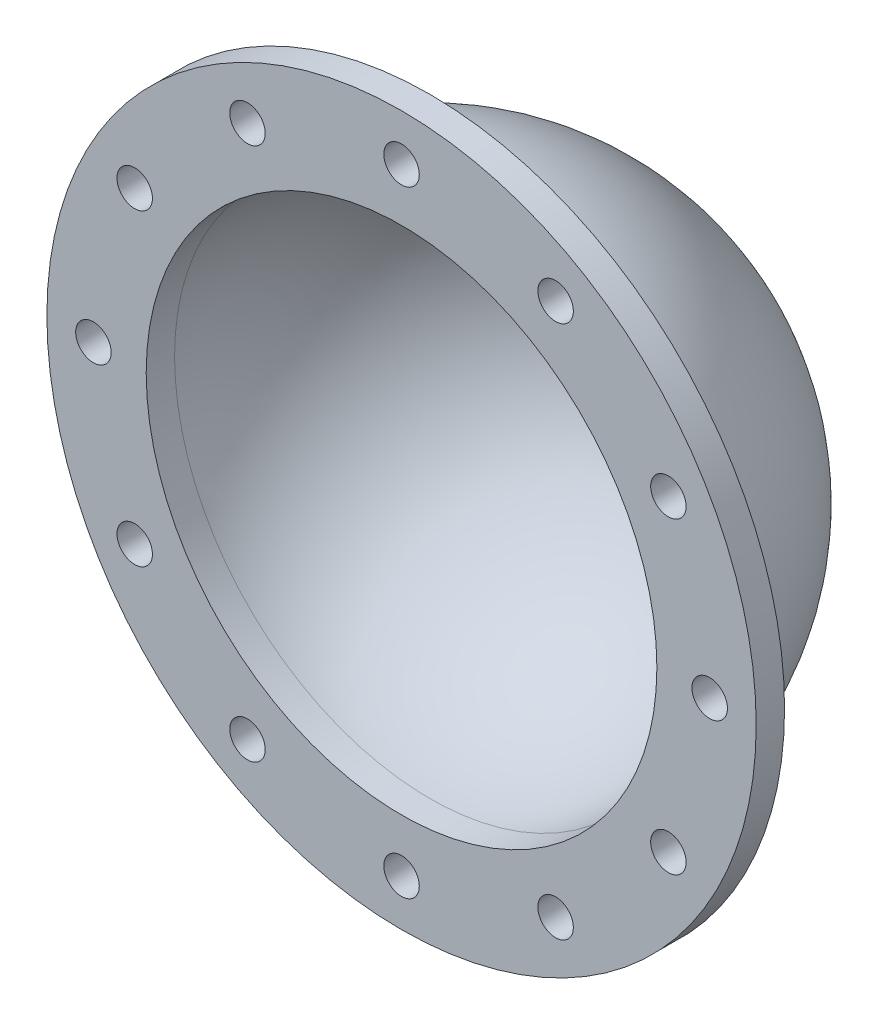
SolidWorks part; units mm, degrees
ref_plane "Front Plane" through (0, 0, 0) normal (0, 0, 1) x (1, 0, 0)
ref_plane "Top Plane" through (0, 0, 0) normal (0, 1, 0) x (1, 0, 0)
ref_plane "Right Plane" through (0, 0, 0) normal (1, 0, 0) x (0, 0, -1)
sketch "Sketch1" plane through (0, 0, 0) normal (0, 0, 1) x (1, 0, 0)
  line L0 (0, 250) -> (0, 229.7001) construction
  line L1 (0, 229.7001) -> (0, 204.7001) construction
  circle A0 centre (0, 0) radius 250
  circle A1 centre (0, 0) radius 180
  circle A2 centre (0, 217.2001) radius 12.5
  circle A3 centre (108.6, 188.1008) radius 12.5
  circle A4 centre (188.1008, 108.6) radius 12.5
  circle A5 centre (217.2001, 0) radius 12.5
  circle A6 centre (188.1008, -108.6) radius 12.5
  circle A7 centre (108.6, -188.1008) radius 12.5
  circle A8 centre (0, -217.2001) radius 12.5
  circle A9 centre (-108.6, -188.1008) radius 12.5
  circle A10 centre (-188.1008, -108.6) radius 12.5
  circle A11 centre (-217.2001, 0) radius 12.5
  circle A12 centre (-188.1008, 108.6) radius 12.5
  circle A13 centre (-108.6, 188.1008) radius 12.5
  point P33 (0, 0)
  dimension "D1" = 12
extrude "Boss-Extrude2" add sketch "Sketch1" along normal blind 20
sketch "Sketch2" plane through (0, 0, 0) normal (0, 0, -1) x (-1, 0, 0)
  line L0 (0, 180) -> (0, 200)
  line L1 (0, -180) -> (0, -200)
  arc A0 (0, -180) -> (0, 180) centre (0, 0) ccw
  arc A1 (0, -200) -> (0, 200) centre (0, 0) ccw
revolve "Revolve1" add sketch "Sketch2" angle 180 about L0
